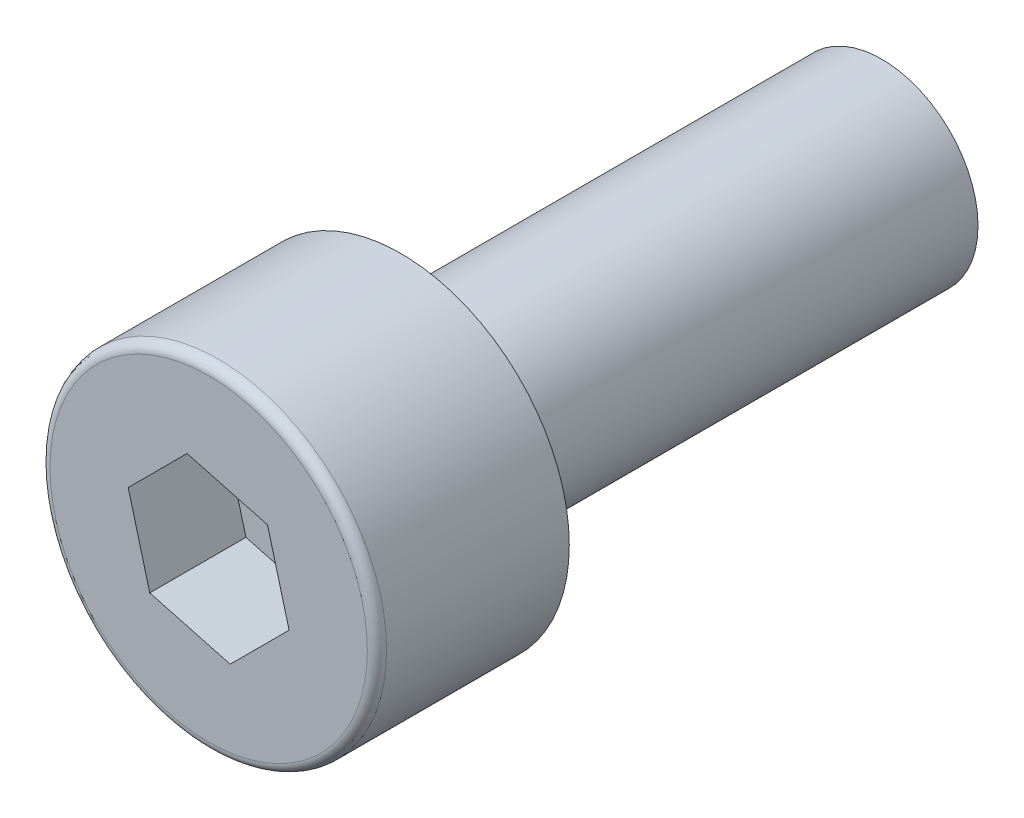
SolidWorks part; units mm, degrees
ref_plane "前视基准面" through (0, 0, 0) normal (0, 0, 1) x (1, 0, 0)
ref_plane "上视基准面" through (0, 0, 0) normal (0, 1, 0) x (1, 0, 0)
ref_plane "右视基准面" through (0, 0, 0) normal (1, 0, 0) x (0, 0, -1)
sketch "草图1" plane through (0, 0, 0) normal (0, 0, 1) x (1, 0, 0)
  circle A0 centre (0, 0) radius 3.5
  dimension "D1" = 7
extrude "凸台-拉伸1" add sketch "草图1" along normal blind 4
sketch "草图2" plane through (0, 0, 4) normal (0, 0, 1) x (1, 0, 0)
  line L1 (-1.2247, -1.2247) -> (0.4483, -1.673)
  line L2 (0.4483, -1.673) -> (1.673, -0.4483)
  line L3 (1.673, -0.4483) -> (1.2247, 1.2247)
  line L4 (1.2247, 1.2247) -> (-0.4483, 1.673)
  line L5 (-0.4483, 1.673) -> (-1.673, 0.4483)
  line L6 (-1.673, 0.4483) -> (-1.2247, -1.2247)
  circle A0 centre (0, 0) radius 1.5 construction
  dimension "D1" = 3
extrude "切除-拉伸1" cut sketch "草图2" against normal blind 2
sketch "草图3" plane through (0, 0, 0) normal (0, 0, -1) x (-1, 0, 0)
  circle A0 centre (0, 0) radius 2
  dimension "D1" = 4
extrude "凸台-拉伸2" add sketch "草图3" along normal blind 10
fillet "圆角1" radius 0.2 1 edges at (3.5, 0, 4)
